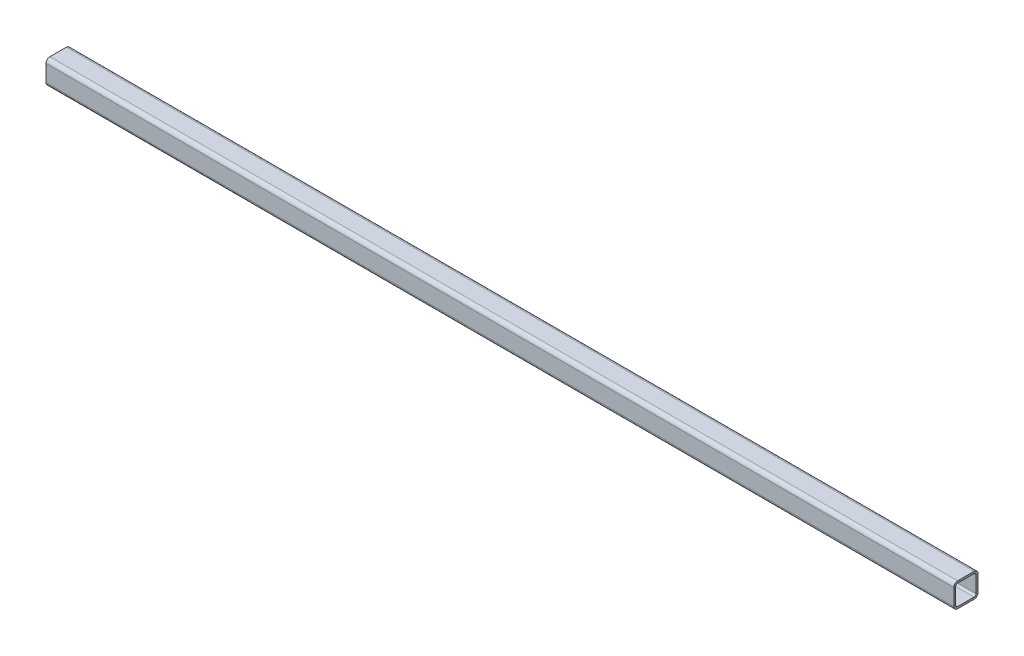
SolidWorks part; units mm, degrees
ref_plane "Front Plane" through (0, 0, 0) normal (0, 0, 1) x (1, 0, 0)
ref_plane "Top Plane" through (0, 0, 0) normal (0, 1, 0) x (1, 0, 0)
ref_plane "Right Plane" through (0, 0, 0) normal (1, 0, 0) x (0, 0, -1)
sketch "Sketch1" plane through (0, 0, 0) normal (0, 1, 0) x (1, 0, 0)
  line L0 (0, 0) -> (1500, 0)
  dimension "D1" = 1500
other "Tube (square) 40 X 40 X 3.2(7)"
ref_plane "Plane1" through (0, 0, 0) normal (1, 0, 0) x (0, 0, -1)
sketch "Sketch12" plane through (0, 0, 0) normal (1, 0, 0) x (0, 0, -1)
  line L0 (-13.6, -16.8) -> (13.6, -16.8)
  line L1 (-16.8, -13.6) -> (-16.8, 13.6)
  line L2 (13.6, 16.8) -> (-13.6, 16.8)
  line L3 (16.8, 13.6) -> (16.8, -13.6)
  line L4 (-13.6, -20) -> (13.6, -20)
  line L5 (-20, -13.6) -> (-20, 13.6)
  line L6 (13.6, 20) -> (-13.6, 20)
  line L7 (20, 13.6) -> (20, -13.6)
  line L8 (-20, 0) -> (-16.8, 0) construction
  line L9 (-16.8, 0) -> (16.8, 0) construction
  line L10 (16.8, 0) -> (20, 0) construction
  line L12 (0, 20) -> (0, 16.8) construction
  line L13 (0, 16.8) -> (0, -16.8) construction
  line L14 (0, -16.8) -> (0, -20) construction
  arc A0 (20, 13.6) -> (13.6, 20) centre (13.6, 13.6) ccw
  arc A1 (13.6, -20) -> (20, -13.6) centre (13.6, -13.6) ccw
  arc A2 (-20, -13.6) -> (-13.6, -20) centre (-13.6, -13.6) ccw
  arc A3 (-13.6, 20) -> (-20, 13.6) centre (-13.6, 13.6) ccw
  arc A4 (-13.6, 16.8) -> (-16.8, 13.6) centre (-13.6, 13.6) ccw
  arc A5 (16.8, 13.6) -> (13.6, 16.8) centre (13.6, 13.6) ccw
  arc A6 (13.6, -16.8) -> (16.8, -13.6) centre (13.6, -13.6) ccw
  arc A7 (-16.8, -13.6) -> (-13.6, -16.8) centre (-13.6, -13.6) ccw
  point P2 (-20, 20)
  point P33 (-20, -20)
  point P34 (20, -20)
  point P36 (20, 20)
  point P37 (0, 0)
  dimension "D1" = 6.4
  dimension "Thickness" = 3.2
  dimension "V_leg" = 40
  dimension "H_leg" = 40
